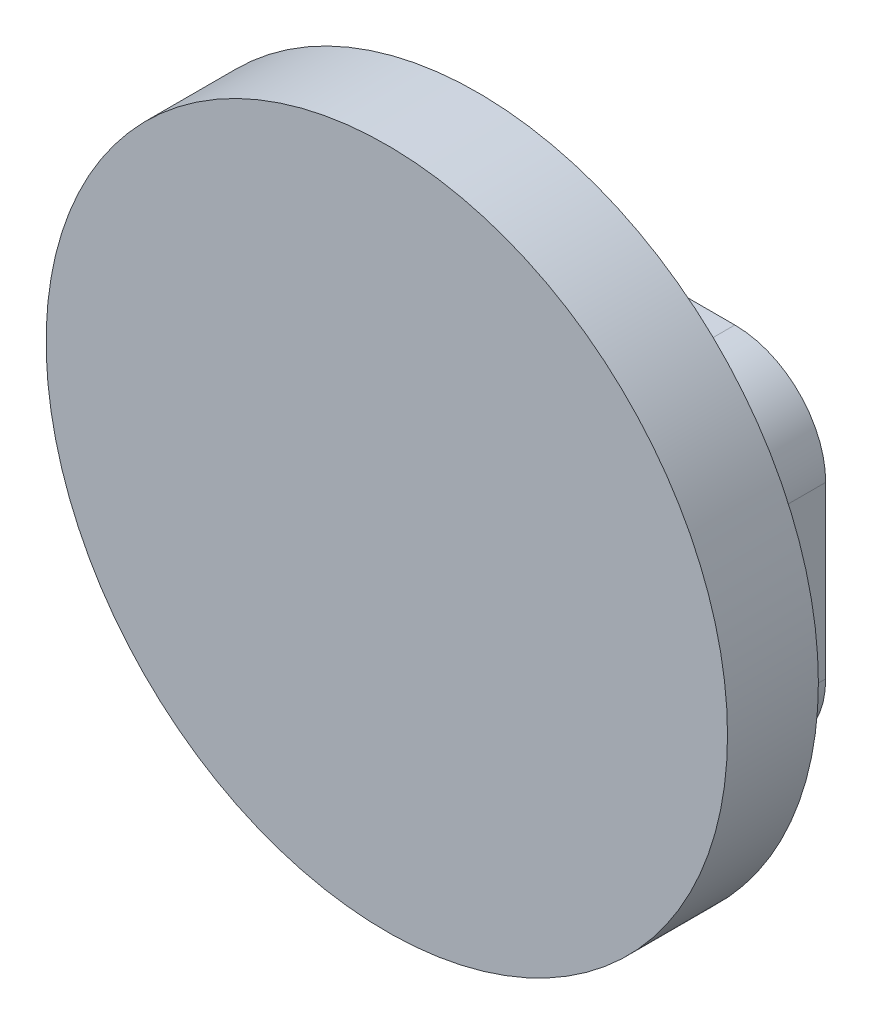
SolidWorks part; units mm, degrees
ref_plane "Front Plane" through (0, 0, 0) normal (0, 0, 1) x (1, 0, 0)
ref_plane "Top Plane" through (0, 0, 0) normal (0, 1, 0) x (1, 0, 0)
ref_plane "Right Plane" through (0, 0, 0) normal (1, 0, 0) x (0, 0, -1)
sketch "Sketch1" plane through (0, 0, 0) normal (0, 0, 1) x (1, 0, 0)
  circle A0 centre (11.9455, 0) radius 37.5
  dimension "D1" = 75
extrude "Boss-Extrude1" add sketch "Sketch1" along normal blind 10
sketch "Sketch2" plane through (0, 0, 0) normal (0, 0, -1) x (-1, 0, 0)
  line L4 (-35.25, -14.25) -> (11.25, -14.2)
  line L5 (84.5, -14.2) -> (86.9, -14.2) construction
  line L6 (11.25, -14.2) -> (11.25, 14.4843)
  line L7 (-35.25, 14.4843) -> (-35.25, -14.25)
  line L8 (-35.25, 14.4843) -> (11.25, 14.4843)
  line L9 (-30.25, 19.4843) -> (6.25, 19.4843)
  line L10 (16.25, -9.2054) -> (16.25, 9.4843)
  line L11 (-30.2392, -19.2446) -> (6.2608, -19.2054)
  line L12 (-40.25, 9.4843) -> (-40.25, -9.2446)
  line L13 (-40.25, -19.2554) -> (16.25, -19.1946) construction
  line L14 (-40.25, 19.4843) -> (-40.25, -19.2554) construction
  line L15 (16.25, -19.1946) -> (16.25, 19.4843) construction
  line L16 (-40.25, 19.4843) -> (16.25, 19.4843) construction
  arc A2 (-30.2392, -19.2446) -> (-40.25, -9.2446) centre (-30.25, -9.2446) cw
  arc A3 (16.25, -9.2054) -> (6.2608, -19.2054) centre (6.25, -9.2054) cw
  arc A4 (6.25, 19.4843) -> (16.25, 9.4843) centre (6.25, 9.4843) cw
  arc A5 (-30.25, 19.4843) -> (-40.25, 9.4843) centre (-30.25, 9.4843) ccw
  dimension "D2" = 10
  dimension "D1" = 5
extrude "Boss-Extrude2" add sketch "Sketch2" along normal blind 10
